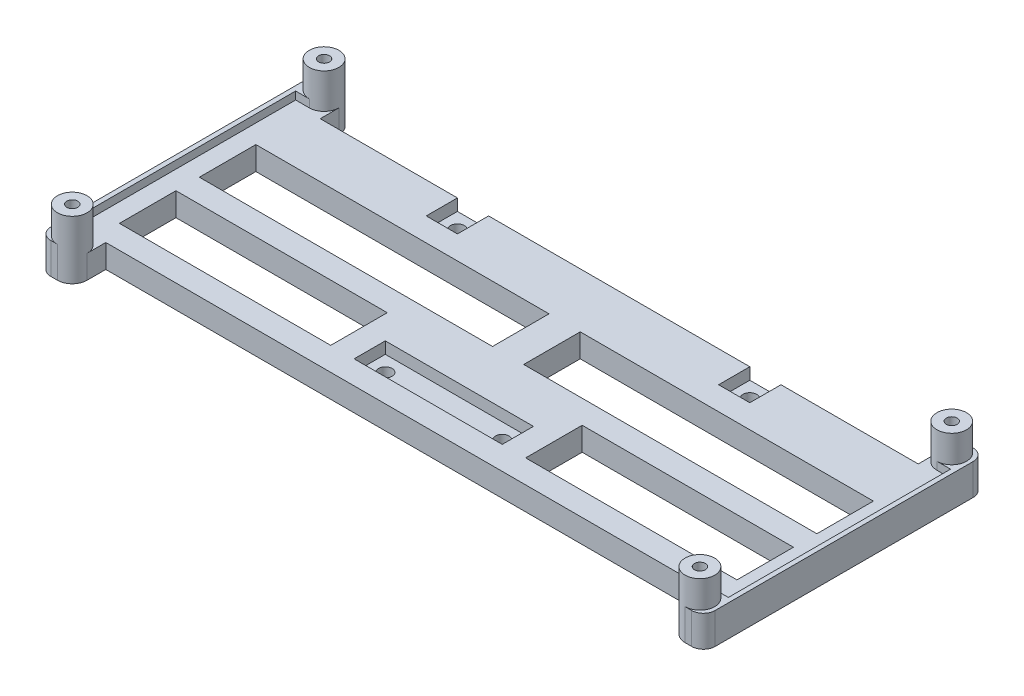
SolidWorks part; units mm, degrees
material "S235JR"
ref_plane "Piano X" through (0, 0, 0) normal (0, 0, 1) x (1, 0, 0)
ref_plane "Piano Y" through (0, 0, 0) normal (0, 1, 0) x (1, 0, 0)
ref_plane "Piano Z" through (0, 0, 0) normal (1, 0, 0) x (0, 0, -1)
sketch "Schizzo1" plane through (0, 0, 0) normal (0, 1, 0) x (1, 0, 0)
  line L0 (-76.7, -27.5) -> (-76.7, -32.3)
  line L1 (-76.7, -27.5) -> (76.7, -27.5)
  line L2 (-85.2, -36.1) -> (-85.2, 36.1)
  line L3 (-76.7, 27.5) -> (76.7, 27.5)
  line L4 (85.2, -36.1) -> (85.2, 36.1)
  line L5 (0, 27.5) -> (0, -27.5) construction
  line L6 (-85.2, 0) -> (85.2, 0) construction
  line L7 (76.7, -27.5) -> (76.7, -32.3)
  line L8 (76.7, 27.5) -> (76.7, 32.3)
  line L9 (-76.7, 27.5) -> (-76.7, 32.3)
  line L10 (80.5, -36.1) -> (85.2, -36.1)
  line L11 (80.5, 36.1) -> (85.2, 36.1)
  line L12 (-80.5, 36.1) -> (-85.2, 36.1)
  line L13 (-80.5, -36.1) -> (-85.2, -36.1)
  line L14 (76.7, 27.5) -> (80.5, 27.5) construction
  line L15 (80.5, 27.5) -> (80.5, 32.3) construction
  line L16 (80.5, 32.3) -> (80.5, 36.1) construction
  arc A0 (-80.5, 36.1) -> (-76.7, 32.3) centre (-80.5, 32.3) cw
  arc A1 (-80.5, -36.1) -> (-76.7, -32.3) centre (-80.5, -32.3) ccw
  arc A2 (76.7, -32.3) -> (80.5, -36.1) centre (80.5, -32.3) ccw
  arc A3 (80.5, 36.1) -> (76.7, 32.3) centre (80.5, 32.3) ccw
  circle A4 centre (-80.5, 32.3) radius 1.4
  circle A5 centre (-80.5, -32.3) radius 1.4
  circle A6 centre (80.5, -32.3) radius 1.4
  circle A7 centre (80.5, 32.3) radius 1.4
  point P0 (0, 0)
  dimension "D5" = 2.8
  dimension "D2" = 55
  dimension "D1" = 161
  dimension "D6" = 4.7
  dimension "D3" = 2.4
  dimension "D4" = 4.8
extrude "Estrusione-Estrusione1" add sketch "Schizzo1" along normal blind 6
sketch "Schizzo2" plane through (0, 6, 0) normal (0, 1, 0) x (1, 0, 0)
  circle A0 centre (-80.5, 32.3) radius 3.8
  circle A1 centre (-80.5, -32.3) radius 3.8
  circle A2 centre (80.5, -32.3) radius 3.8
  circle A3 centre (80.5, 32.3) radius 3.8
  circle A4 centre (-80.5, 32.3) radius 1.4 construction
  circle A5 centre (-80.5, -32.3) radius 1.4 construction
  circle A6 centre (80.5, -32.3) radius 1.4 construction
  circle A7 centre (80.5, 32.3) radius 1.4 construction
  circle A8 centre (-80.5, 32.3) radius 1.4
  circle A9 centre (-80.5, -32.3) radius 1.4
  circle A10 centre (80.5, -32.3) radius 1.4
  circle A11 centre (80.5, 32.3) radius 1.4
  arc A12 (76.7, -32.3) -> (80.5, -36.1) centre (80.5, -32.3) ccw construction
  arc A13 (-76.7, 32.3) -> (-80.5, 36.1) centre (-80.5, 32.3) ccw construction
  arc A14 (-80.5, -36.1) -> (-76.7, -32.3) centre (-80.5, -32.3) ccw construction
extrude "Estrusione-Estrusione2" add sketch "Schizzo2" along normal blind 9
sketch "Schizzo3" plane through (0, 6, 0) normal (0, 1, 0) x (1, 0, 0)
  line L0 (-37.5, 23.5) -> (37.5, 23.5) construction
  line L1 (-15, -17.5) -> (15, -17.5) construction
  line L2 (0, -17.5) -> (0, 23.5) construction
  line L3 (-76.7, -27.5) -> (76.7, -27.5) construction
  line L4 (76.7, 27.5) -> (-76.7, 27.5) construction
  circle A0 centre (-37.5, 23.5) radius 1.75
  circle A1 centre (-15, -17.5) radius 1.75
  circle A2 centre (15, -17.5) radius 1.75
  circle A3 centre (37.5, 23.5) radius 1.75
  dimension "D5" = 3.5
  dimension "D1" = 75
  dimension "D2" = 30
  dimension "D3" = 10
  dimension "D4" = 4
extrude "Taglio-Estrusione1" cut sketch "Schizzo3" against normal through all
sketch "Schizzo5" plane through (0, 6, 0) normal (0, 1, 0) x (1, 0, 0)
  line L0 (76.7, 27.5) -> (-76.7, 27.5) construction
  line L1 (41.5, 19.5) -> (33.5, 19.5)
  line L2 (41.5, 19.5) -> (41.5, 27.5)
  line L3 (41.5, 27.5) -> (33.5, 27.5)
  line L4 (-41.5, 19.5) -> (-41.5, 27.5)
  line L6 (41.5, 23.5) -> (-41.5, 23.5) construction
  line L7 (-33.5, 27.5) -> (-41.5, 27.5)
  line L8 (19, -13.5) -> (-19, -13.5)
  line L9 (19, -13.5) -> (19, -21.5)
  line L10 (19, -21.5) -> (-19, -21.5)
  line L11 (-19, -13.5) -> (-19, -21.5)
  line L12 (0, -21.5) -> (0, -13.5) construction
  line L13 (19, -17.5) -> (-19, -17.5) construction
  line L14 (0, -17.5) -> (0, 23.5) construction
  line L15 (-33.5, 19.5) -> (-33.5, 27.5)
  line L16 (33.5, 27.5) -> (33.5, 19.5)
  line L17 (-33.5, 19.5) -> (-41.5, 19.5)
  circle A0 centre (15, -17.5) radius 1.75 construction
  circle A1 centre (37.5, 23.5) radius 1.75 construction
  point P0 (0, 23.5)
  point P6 (0, -17.5)
  dimension "D4" = 4
  dimension "D1" = 4
  dimension "D2" = 8
  dimension "D3" = 4
  dimension "D5" = 8
  dimension "D6" = 8
extrude "Taglio-Estrusione2" cut sketch "Schizzo5" against normal blind 3
sketch "Schizzo6" plane through (0, 6, 0) normal (0, 1, 0) x (1, 0, 0)
  line L0 (33.5, 19.5) -> (41.5, 19.5) construction
  line L1 (-79.2, 13.5) -> (-4, 13.5)
  line L2 (-79.2, 13.5) -> (-79.2, -1)
  line L3 (-79.2, -1) -> (-4, -1)
  line L4 (-4, 13.5) -> (-4, -1)
  line L5 (4, -1) -> (79.2, -1)
  line L6 (4, -1) -> (4, 13.5)
  line L7 (4, 13.5) -> (79.2, 13.5)
  line L8 (79.2, -1) -> (79.2, 13.5)
  line L9 (-79.2, -21.5) -> (-25, -21.5)
  line L10 (-79.2, -21.5) -> (-79.2, -7)
  line L11 (-79.2, -7) -> (-25, -7)
  line L12 (-25, -21.5) -> (-25, -7)
  line L13 (79.2, -21.5) -> (25, -21.5)
  line L14 (79.2, -21.5) -> (79.2, -7)
  line L15 (79.2, -7) -> (25, -7)
  line L16 (25, -21.5) -> (25, -7)
  line L17 (-76.7, -27.5) -> (76.7, -27.5) construction
  line L18 (-19, -13.5) -> (-19, -21.5) construction
  line L19 (19, -21.5) -> (19, -13.5) construction
  line L20 (85.2, -36.1) -> (85.2, 36.1) construction
  line L21 (-85.2, 36.1) -> (-85.2, -36.1) construction
  line L22 (-4, 0) -> (4, 0) construction
  dimension "D1" = 6
  dimension "D2" = 6
  dimension "D3" = 6
  dimension "D4" = 6
  dimension "D5" = 6
  dimension "D6" = 6
  dimension "D7" = 6
  dimension "D8" = 8
extrude "Taglio-Estrusione3" cut sketch "Schizzo6" against normal through all
sketch "Schizzo7" plane through (0, 6, 0) normal (0, 1, 0) x (1, 0, 0)
  line L6 (-80.5, 36.1) -> (-85.2, 36.1)
  line L7 (-85.2, 36.1) -> (-85.2, -36.1)
  line L8 (-85.2, -36.1) -> (-80.5, -36.1)
  line L9 (-80.5, -28.5) -> (-84, -28.5)
  line L10 (-80.5, 28.5) -> (-84, 28.5)
  line L11 (-84, 28.5) -> (-84, -28.5)
  circle A5 centre (-80.5, -32.3) radius 3.8 construction
  arc A6 (-80.5, 36.1) -> (-76.7, 32.3) centre (-80.5, 32.3) ccw construction
  arc A7 (-80.5, -28.5) -> (-80.5, -36.1) centre (-80.5, -32.3) ccw
  arc A8 (-80.5, 36.1) -> (-80.5, 28.5) centre (-80.5, 32.3) ccw
  dimension "D1" = 1.2
extrude "Estrusione-Estrusione4" add sketch "Schizzo7" along normal blind 2
mirror "Specchia3" about plane through (0, 0, 0) normal (1, 0, 0) of "Estrusione-Estrusione4"
fillet "Raccordo1" radius 3 4 edges at (-85.2, 4, -36.1) (-85.2, 4, 36.1) (85.2, 4, -36.1) (85.2, 4, 36.1)
equation "\"D3@Schizzo1\"=0.4*6"
